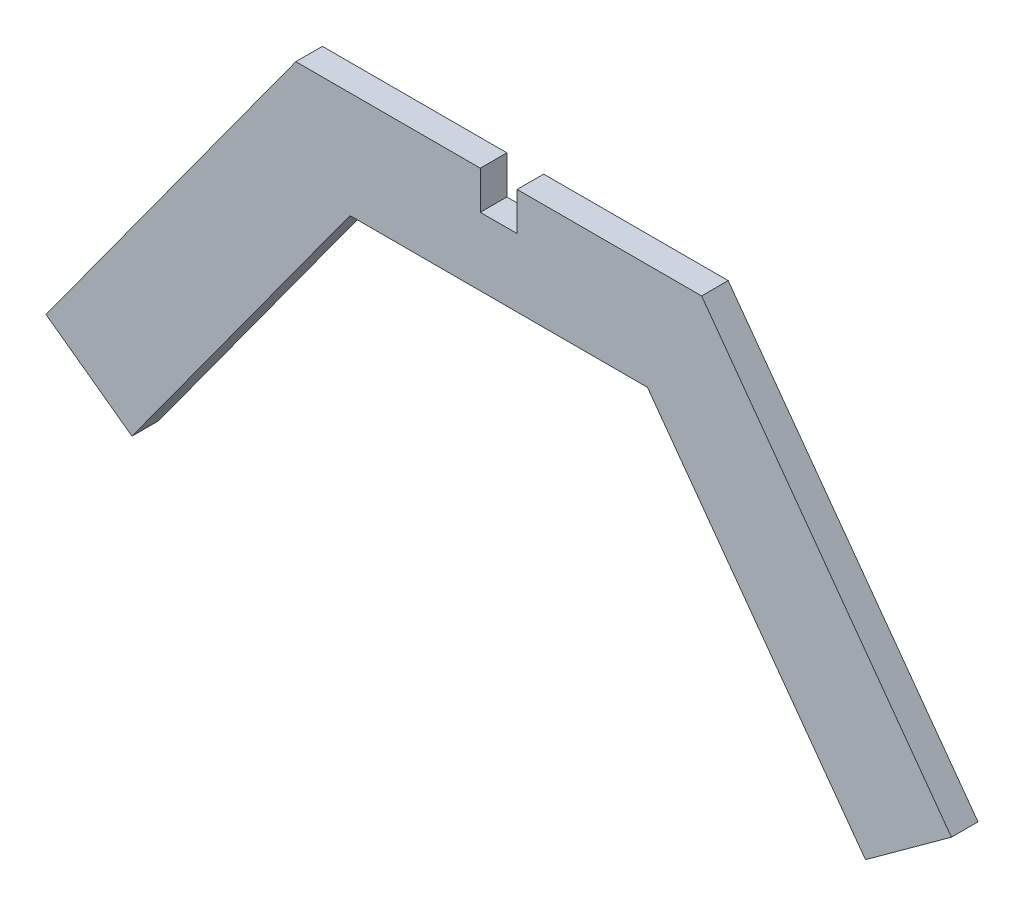
SolidWorks part; units mm, degrees
material "Balsa"
ref_plane "Front Plane" through (0, 0, 0) normal (0, 0, 1) x (1, 0, 0)
ref_plane "Top Plane" through (0, 0, 0) normal (0, 1, 0) x (1, 0, 0)
ref_plane "Right Plane" through (0, 0, 0) normal (1, 0, 0) x (0, 0, -1)
sketch "Sketch1" plane through (0, 0, 0) normal (0, 0, 1) x (1, 0, 0)
  line L0 (0, 0) -> (0, -111.1672) construction
  line L1 (0, 0) -> (110.0329, 0) construction
  line L2 (36.3765, 0) -> (-36.3765, 0)
  line L3 (-36.3765, 0) -> (-81.1657, -61.6471)
  line L4 (-81.1657, -61.6471) -> (-65.7539, -72.8444)
  line L5 (-65.7539, -72.8444) -> (-26.67, -19.05)
  line L6 (-26.67, -19.05) -> (26.67, -19.05)
  line L7 (65.7539, -72.8444) -> (26.67, -19.05)
  line L8 (81.1657, -61.6471) -> (65.7539, -72.8444)
  line L9 (36.3765, 0) -> (81.1657, -61.6471)
  point P15 (0, 0)
  point P16 (0, -19.05)
  dimension "D1" = 19.05
  dimension "0.75" = 19.05
  dimension "D3" = 54
  dimension "D4" = 76.2
  dimension "D5" = 26.67
extrude "Boss-Extrude1" add sketch "Sketch1" along normal blind 4.7625
sketch "Sketch2" plane through (0, 0, 4.7625) normal (0, 0, 1) x (1, 0, 0)
  line L0 (0, 0) -> (0, -19.05) construction
  line L1 (36.3765, 0) -> (-36.3765, 0) construction
  line L2 (-26.67, -19.05) -> (26.67, -19.05) construction
  line L3 (3.302, 0) -> (-3.302, 0)
  line L4 (-3.302, 0) -> (-3.302, -6.858)
  line L5 (-3.302, -6.858) -> (3.302, -6.858)
  line L6 (3.302, 0) -> (3.302, -6.858)
  point P10 (0, -6.858)
  dimension "D1" = 3.302
  dimension "D2" = 6.858
extrude "Cut-Extrude1" cut sketch "Sketch2" against normal through all
